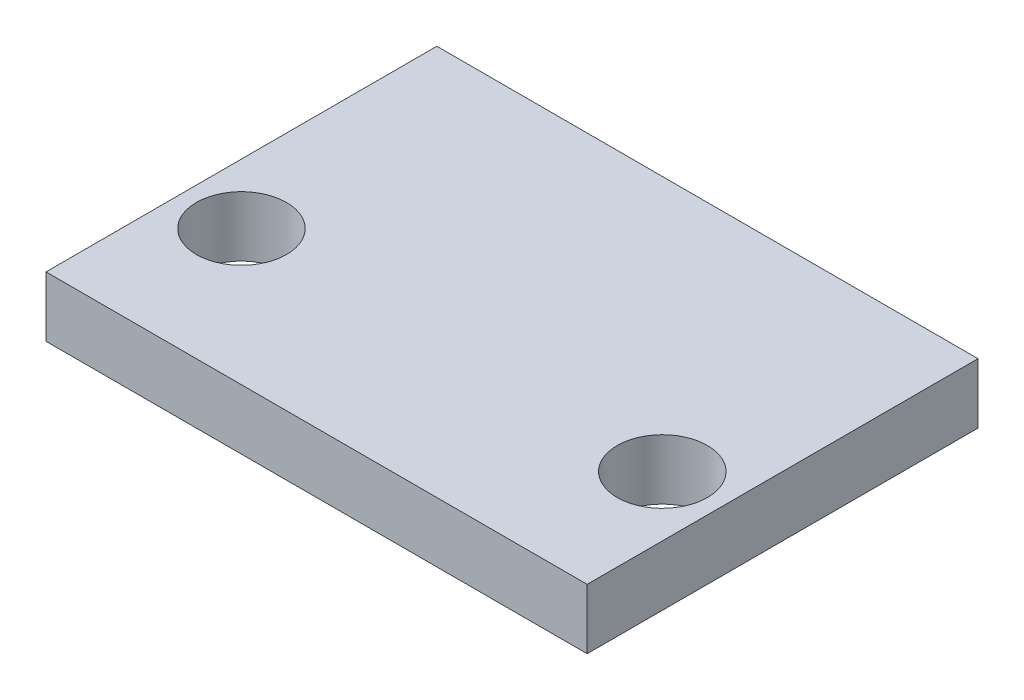
SolidWorks part; units mm, degrees
ref_plane "Спереди" through (0, 0, 0) normal (0, 0, 1) x (1, 0, 0)
ref_plane "Сверху" through (0, 0, 0) normal (0, 1, 0) x (1, 0, 0)
ref_plane "Справа" through (0, 0, 0) normal (1, 0, 0) x (0, 0, -1)
sketch "Эскиз1" plane through (0, 0, 0) normal (0, 1, 0) x (1, 0, 0)
  line L1 (0, 0) -> (18, 0)
  line L2 (0, 0) -> (0, -13)
  line L3 (0, -13) -> (18, -13)
  line L4 (18, 0) -> (18, -13)
  dimension "D1" = 13
  dimension "D2" = 18
extrude "Бобышка-Вытянуть1" add sketch "Эскиз1" along normal blind 2
sketch "Эскиз2" plane through (0, 2, 0) normal (0, 1, 0) x (1, 0, 0)
  line L0 (18, -13) -> (18, 0) construction
  line L1 (0, 0) -> (18, 0)
  line L2 (0, 0) -> (0, -3)
  line L3 (0, -3) -> (18, -3)
  line L4 (18, 0) -> (18, -3)
  dimension "D1" = 3
sketch "Эскиз3" plane through (0, 0, 0) normal (0, -1, 0) x (1, 0, 0)
  line L0 (0, 13) -> (18, 13) construction
  line L1 (0, 0) -> (0, 13) construction
  line L2 (9, 13) -> (9, 0) construction
  line L3 (18, 0) -> (0, 0) construction
  circle A0 centre (2, 8.5) radius 1.5
  circle A1 centre (16, 8.5) radius 1.5
  dimension "D1" = 3
  dimension "D2" = 4.5
  dimension "D3" = 2
extrude "Вырез-Вытянуть1" cut sketch "Эскиз3" against normal blind 8
